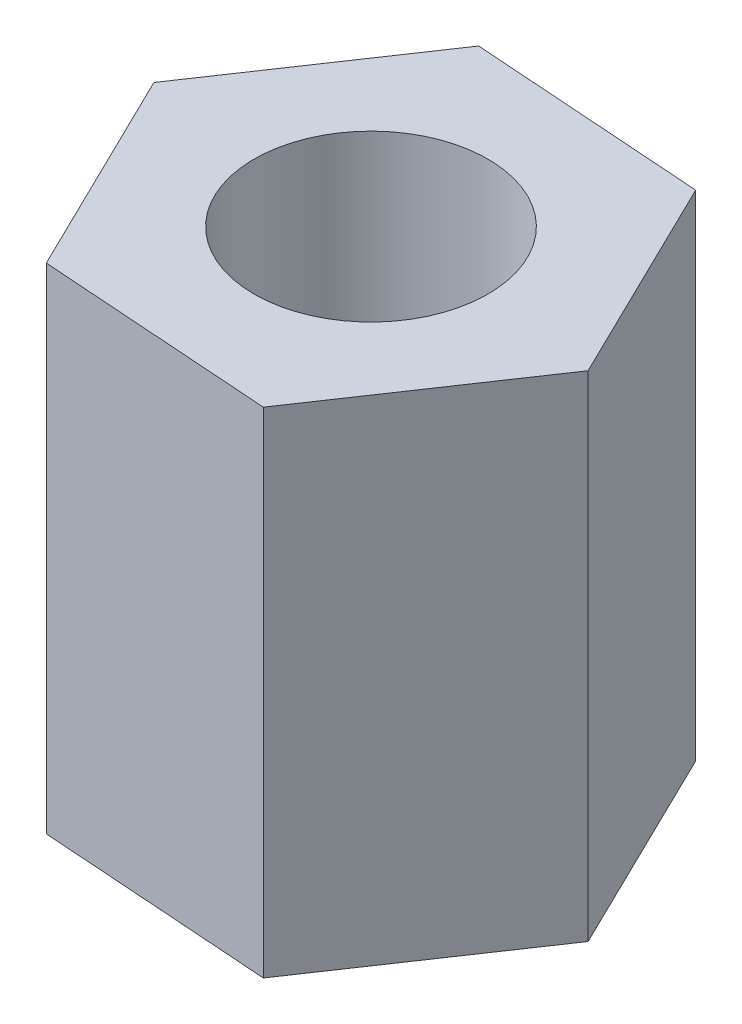
SolidWorks part; units mm, degrees
ref_plane "前视基准面" through (0, 0, 0) normal (0, 0, 1) x (1, 0, 0)
ref_plane "上视基准面" through (0, 0, 0) normal (0, 1, 0) x (1, 0, 0)
ref_plane "右视基准面" through (0, 0, 0) normal (1, 0, 0) x (0, 0, -1)
sketch "草图1" plane through (0, 0, 0) normal (0, 1, 0) x (1, 0, 0)
  line L1 (-2.9927, 0.2088) -> (-1.6772, -2.4874)
  line L2 (-1.6772, -2.4874) -> (1.3155, -2.6962)
  line L3 (1.3155, -2.6962) -> (2.9927, -0.2088)
  line L4 (2.9927, -0.2088) -> (1.6772, 2.4874)
  line L5 (1.6772, 2.4874) -> (-1.3155, 2.6962)
  line L6 (-1.3155, 2.6962) -> (-2.9927, 0.2088)
  circle A0 centre (0, 0) radius 2.5981 construction
  circle A1 centre (0, 0) radius 1.5
  dimension "D2" = 3
  dimension "D1" = 6
extrude "凸台-拉伸1" add sketch "草图1" along normal blind 6.34
